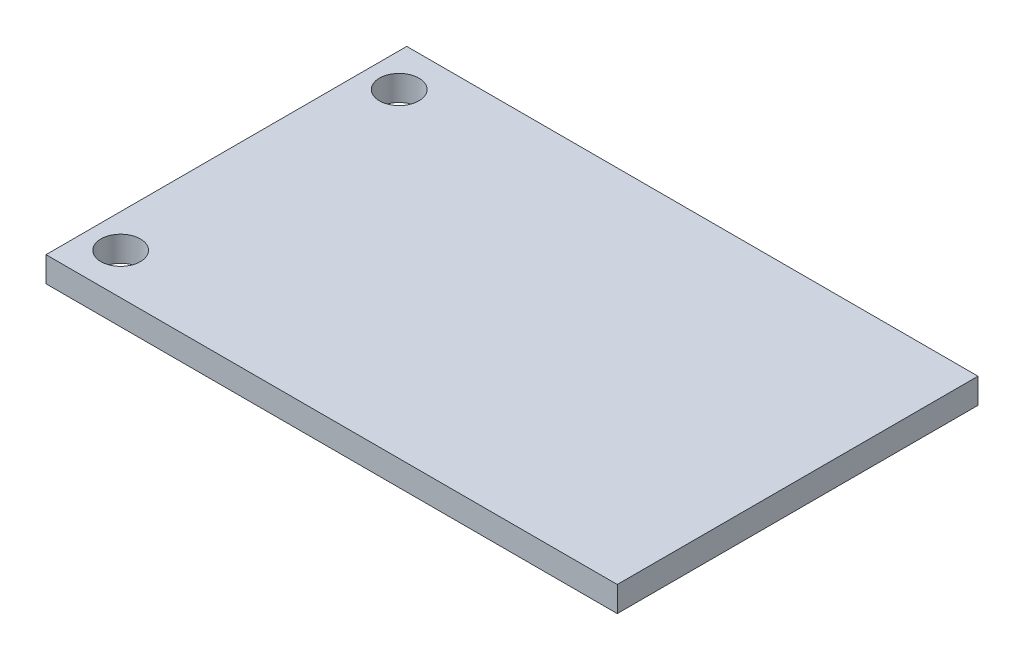
SolidWorks part; units mm, degrees
ref_plane "Front Plane" through (0, 0, 0) normal (0, 0, 1) x (1, 0, 0)
ref_plane "Top Plane" through (0, 0, 0) normal (0, 1, 0) x (1, 0, 0)
ref_plane "Right Plane" through (0, 0, 0) normal (1, 0, 0) x (0, 0, -1)
sketch "Sketch1" plane through (0, 0, 0) normal (0, 1, 0) x (1, 0, 0)
  line L0 (0, 11.43) -> (0, -11.43) construction
  line L1 (-18.1, 11.43) -> (18.1, 11.43)
  line L2 (-18.1, 11.43) -> (-18.1, -11.43)
  line L3 (-18.1, -11.43) -> (18.1, -11.43)
  line L4 (18.1, 11.43) -> (18.1, -11.43)
  line L5 (-18.1, 0) -> (18.1, 0) construction
  circle A0 centre (-15.9748, 8.825) radius 1.25
  circle A1 centre (-15.9748, -8.825) radius 1.25
  point P13 (0, 0)
  point P14 (0, 0)
  point P15 (0, 0)
  dimension "D3" = 2.5
  dimension "D4" = 2.5
  dimension "D1" = 36.2
  dimension "D2" = 22.86
  dimension "D5" = 17.65
extrude "Boss-Extrude1" add sketch "Sketch1" along normal blind 1.6
